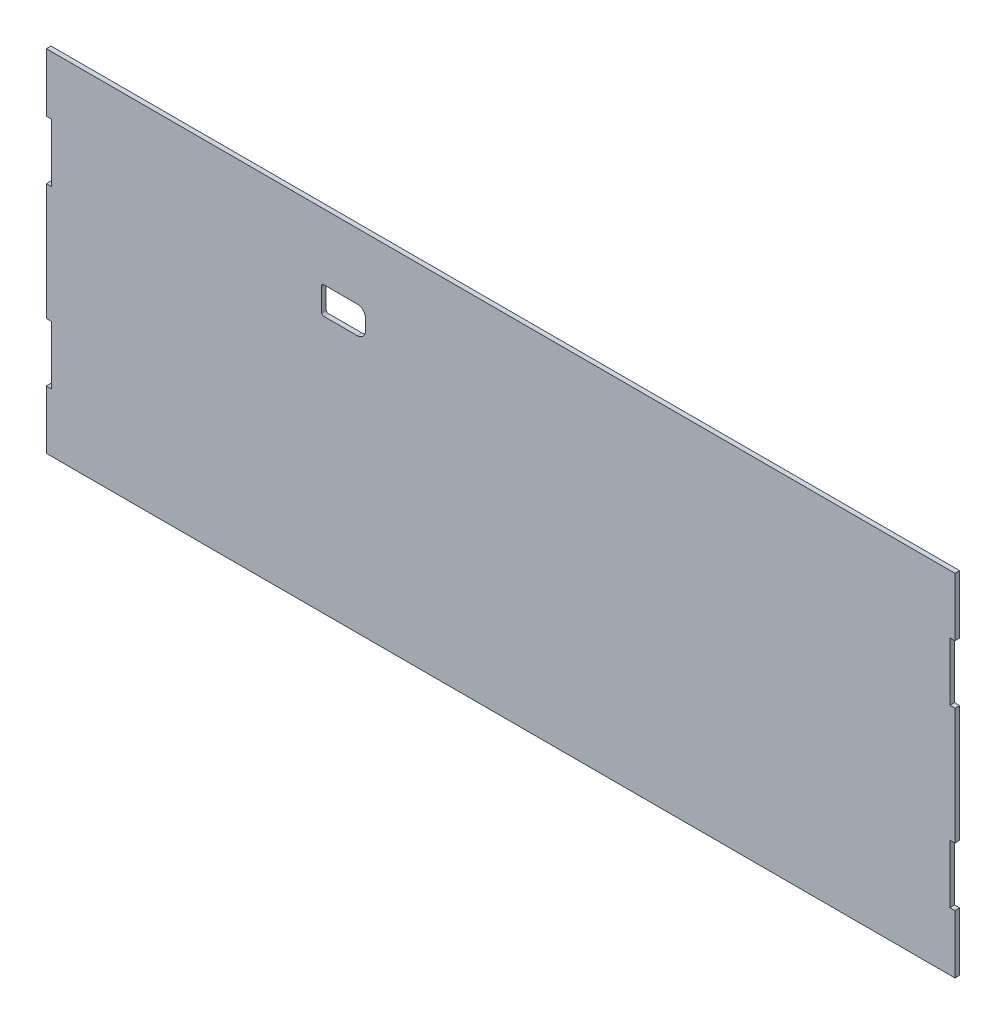
SolidWorks part; units mm, degrees
ref_plane "Front Plane" through (0, 0, 0) normal (0, 0, 1) x (1, 0, 0)
ref_plane "Top Plane" through (0, 0, 0) normal (0, 1, 0) x (1, 0, 0)
ref_plane "Right Plane" through (0, 0, 0) normal (1, 0, 0) x (0, 0, -1)
sketch "Sketch1" plane through (0, 0, 0) normal (0, 0, 1) x (1, 0, 0)
  line L1 (-194.45, 75) -> (194.45, 75)
  line L2 (-194.45, 75) -> (-194.45, -75)
  line L3 (-194.45, -75) -> (194.45, -75)
  line L4 (194.45, 75) -> (194.45, -75)
  line L5 (-194.45, 75) -> (194.45, -75) construction
  line L6 (-194.45, -75) -> (194.45, 75) construction
  point P0 (0, 0)
  dimension "D1" = 150
  dimension "D2" = 388.9
extrude "Boss-Extrude1" add sketch "Sketch1" along normal blind 2
sketch "Sketch2" plane through (0, 0, 2) normal (0, 0, 1) x (1, 0, 0)
  line L0 (-194.45, 75) -> (-194.45, 50)
  line L17 (-200.1317, -75) -> (-200.1317, 75)
  line L33 (-194.45, 50) -> (-192.25, 50)
  line L34 (-192.25, 50) -> (-192.25, 25)
  line L36 (-192.25, 25) -> (-194.45, 25)
  line L37 (-194.45, 75) -> (-194.45, -75) construction
  line L38 (-194.45, 25) -> (-194.45, -25)
  line L40 (-192.25, -25) -> (-192.25, -50)
  line L41 (-194.45, -25) -> (-192.25, -25)
  line L42 (-192.25, -50) -> (-194.45, -50)
  line L43 (-194.45, -50) -> (-194.45, -75)
  line L44 (-194.45, -75) -> (-200.1317, -75)
  line L45 (194.45, -75) -> (194.45, -50)
  line L46 (200.1317, 75) -> (200.1317, -75)
  line L47 (194.45, -50) -> (192.25, -50)
  line L48 (192.25, -50) -> (192.25, -25)
  line L49 (192.25, -25) -> (194.45, -25)
  line L50 (194.45, -25) -> (194.45, 25)
  line L51 (192.25, 25) -> (192.25, 50)
  line L52 (194.45, 25) -> (192.25, 25)
  line L53 (192.25, 50) -> (194.45, 50)
  line L54 (194.45, 50) -> (194.45, 75)
  line L55 (194.45, 75) -> (200.1317, 75)
  line L56 (-200.1317, 75) -> (-194.45, 75)
  line L57 (194.45, -75) -> (200.1317, -75)
  dimension "D1" = 2.2
  dimension "D2" = 25
  dimension "D3" = 50
  dimension "D4" = 25
  dimension "D5" = 25
  dimension "D6" = 25
  dimension "D7" = 2.2
  dimension "D8" = 25
  dimension "D9" = 50
  dimension "D10" = 25
extrude "Cut-Extrude1" cut sketch "Sketch2" against normal blind 2
sketch "Sketch3" plane through (0, 0, 2) normal (0, 0, 1) x (1, 0, 0)
  line L0 (-61.379, 35.1823) -> (-75.654, 35.1823)
  line L1 (-75.654, 46.8823) -> (-61.379, 46.8823)
  line L2 (-76.654, 36.1823) -> (-76.654, 45.8823)
  line L3 (-57.854, 38.7073) -> (-57.854, 43.3573)
  arc A0 (-57.854, 38.7073) -> (-61.379, 35.1823) centre (-61.379, 38.7073) cw
  arc A1 (-57.854, 43.3573) -> (-61.379, 46.8823) centre (-61.379, 43.3573) ccw
  arc A2 (-75.654, 35.1823) -> (-76.654, 36.1823) centre (-75.654, 36.1823) cw
  arc A3 (-76.654, 45.8823) -> (-75.654, 46.8823) centre (-75.654, 45.8823) cw
extrude "Cut-Extrude2" cut sketch "Sketch3" against normal blind 10
